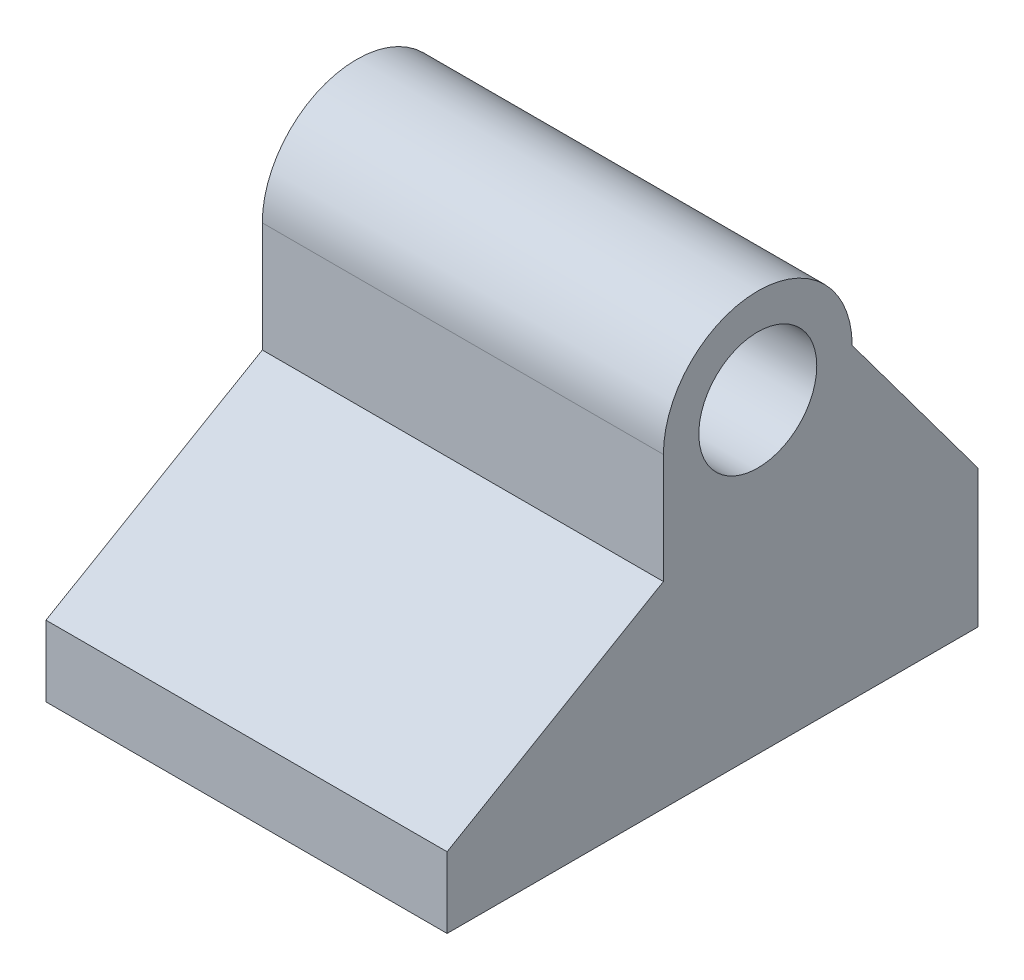
SolidWorks part; units mm, degrees
ref_plane "Спереди" through (0, 0, 0) normal (0, 0, 1) x (1, 0, 0)
ref_plane "Сверху" through (0, 0, 0) normal (0, 1, 0) x (1, 0, 0)
ref_plane "Справа" through (0, 0, 0) normal (1, 0, 0) x (0, 0, -1)
sketch "Эскиз1" plane through (0, 0, 0) normal (1, 0, 0) x (0, 0, -1)
  line L1 (0, 0) -> (0, 35)
  line L2 (0, 35) -> (-32, 78)
  line L3 (-135, 0) -> (-135, 18)
  line L4 (-135, 18) -> (-80, 50)
  line L5 (-80, 50) -> (-80, 78)
  line L6 (0, 0) -> (-135, 0)
  arc A1 (-80, 78) -> (-32, 78) centre (-56, 78) cw
  circle A2 centre (-56, 78) radius 15
  dimension "D7" = 30
  dimension "D8" = 24
  dimension "D1" = 35
  dimension "D2" = 135
  dimension "D3" = 18
  dimension "D4" = 50
  dimension "D5" = 55
  dimension "D6" = 78
sketch "Эскиз3" plane through (0, 0, 0) normal (0, 1, 0) x (1, 0, 0)
  line L0 (10.6332, 0) -> (0.6332, 0)
  line L1 (70.6332, 0) -> (34.6332, 0)
  line L6 (61.6332, -125.0778) -> (43.6332, -125.0778)
  line L12 (10.6332, -80.0778) -> (10.6332, -135.0778)
  line L14 (92.6332, -135.0778) -> (92.6332, -80.0778)
  line L15 (10.6332, -32) -> (10.6332, 0)
  line L17 (92.6332, 0) -> (92.6332, -32)
  line L22 (34.6332, 0) -> (34.6332, -20)
  line L23 (34.6332, -20) -> (70.6332, -20)
  line L24 (70.6332, -20) -> (70.6332, 0)
  line L26 (0.6332, 0) -> (0.6332, -32)
  line L29 (102.6332, -80.0778) -> (102.6332, -135.0778)
  line L30 (43.6332, -125.0778) -> (43.6332, -109.0778)
  line L31 (43.6332, -109.0778) -> (30.1332, -109.0778)
  line L32 (61.6332, -125.0778) -> (61.6332, -109.0778)
  line L33 (61.6332, -109.0778) -> (75.1332, -109.0778)
  line L34 (30.1332, -89.0778) -> (75.1332, -89.0778)
  line L35 (102.6332, -135.0778) -> (92.6332, -135.0778)
  line L36 (102.6332, -80.0778) -> (92.6332, -80.0778)
  line L38 (10.6332, -80.0778) -> (0.6332, -80.0778)
  line L39 (0.6332, -135.0778) -> (10.6332, -135.0778)
  line L40 (0.6332, -80.0778) -> (0.6332, -135.0778)
  line L41 (10.6332, -32) -> (0.6332, -32)
  line L42 (92.6332, 0) -> (102.6332, 0)
  line L43 (102.6332, 0) -> (102.6332, -32)
  line L44 (92.6332, -32) -> (102.6332, -32)
  circle A0 centre (52.6332, -56.6536) radius 15
  arc A1 (75.1332, -89.0778) -> (75.1332, -109.0778) centre (75.1332, -99.0778) cw
  arc A2 (30.1332, -89.0778) -> (30.1332, -109.0778) centre (30.1332, -99.0778) ccw
  point P38 (0.3059, 4.8619)
  point P48 (75.1332, -99.0778)
  point P49 (30.1332, -99.0778)
  dimension "D1" = 102
extrude "Бобышка-Вытянуть3" add sketch "Эскиз1" along normal blind 102 from vertex at 0.6332 starting at point (0.6332, 0, 0)
